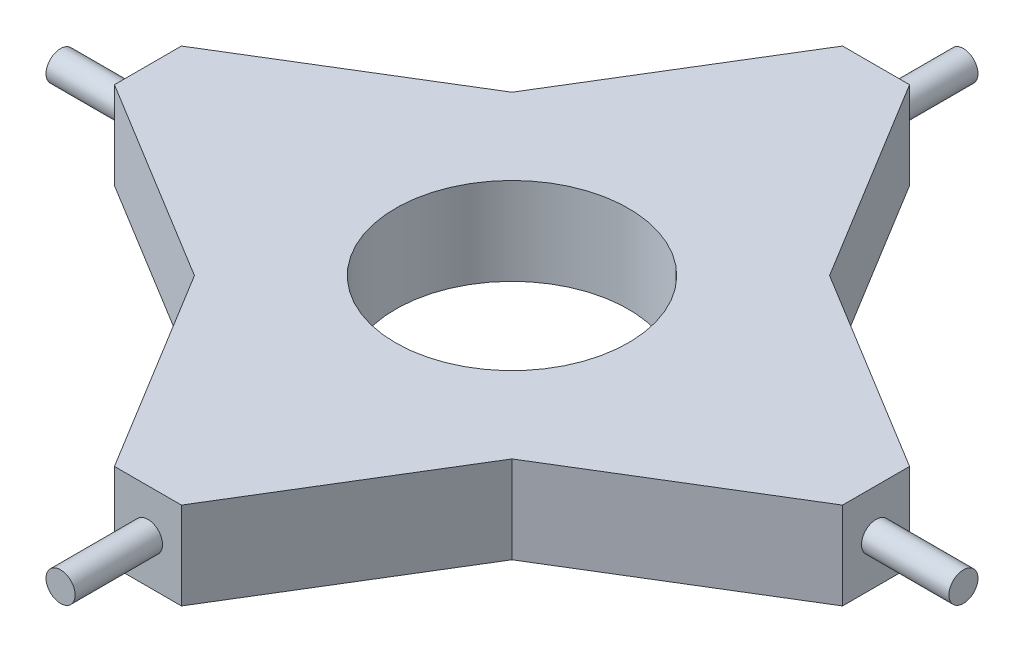
SolidWorks part; units mm, degrees
ref_plane "Front Plane" through (0, 0, 0) normal (0, 0, 1) x (1, 0, 0)
ref_plane "Top Plane" through (0, 0, 0) normal (0, 1, 0) x (1, 0, 0)
ref_plane "Right Plane" through (0, 0, 0) normal (1, 0, 0) x (0, 0, -1)
sketch "Sketch1" plane through (0, 0, 0) normal (0, 1, 0) x (1, 0, 0)
  line L0 (0, 0) -> (0, 125) construction
  line L1 (11.5, 125) -> (-11.5, 125)
  line L2 (-11.5, 125) -> (-54.5185, 54.5185)
  line L3 (11.5, 125) -> (54.5185, 54.5185)
  line L4 (125, 11.5) -> (54.5185, 54.5185)
  line L5 (125, -11.5) -> (125, 11.5)
  line L6 (125, -11.5) -> (54.5185, -54.5185)
  line L7 (11.5, -125) -> (54.5185, -54.5185)
  line L8 (-11.5, -125) -> (11.5, -125)
  line L9 (-11.5, -125) -> (-54.5185, -54.5185)
  line L10 (-125, -11.5) -> (-54.5185, -54.5185)
  line L11 (-125, 11.5) -> (-125, -11.5)
  line L12 (-125, 11.5) -> (-54.5185, 54.5185)
  circle A0 centre (0, 0) radius 40
  point P24 (0, 0)
  dimension "D1" = 80
  dimension "D3" = 125
  dimension "D4" = 11.5
extrude "Boss-Extrude1" add sketch "Sketch1" along normal blind 30
sketch "Sketch2" plane through (0, 0, 125) normal (0, 0, 1) x (1, 0, 0)
  line L0 (0, 0) -> (0, 30) construction
  line L1 (-11.5, 30) -> (11.5, 30) construction
  circle A0 centre (0, 15) radius 5
  dimension "D1" = 10
extrude "Boss-Extrude2" add sketch "Sketch2" along normal blind 30
pattern_circular "CirPattern1" count 4 over 360 about axis through (0, 0, 0) along (0, 1, 0) of "Boss-Extrude2"
